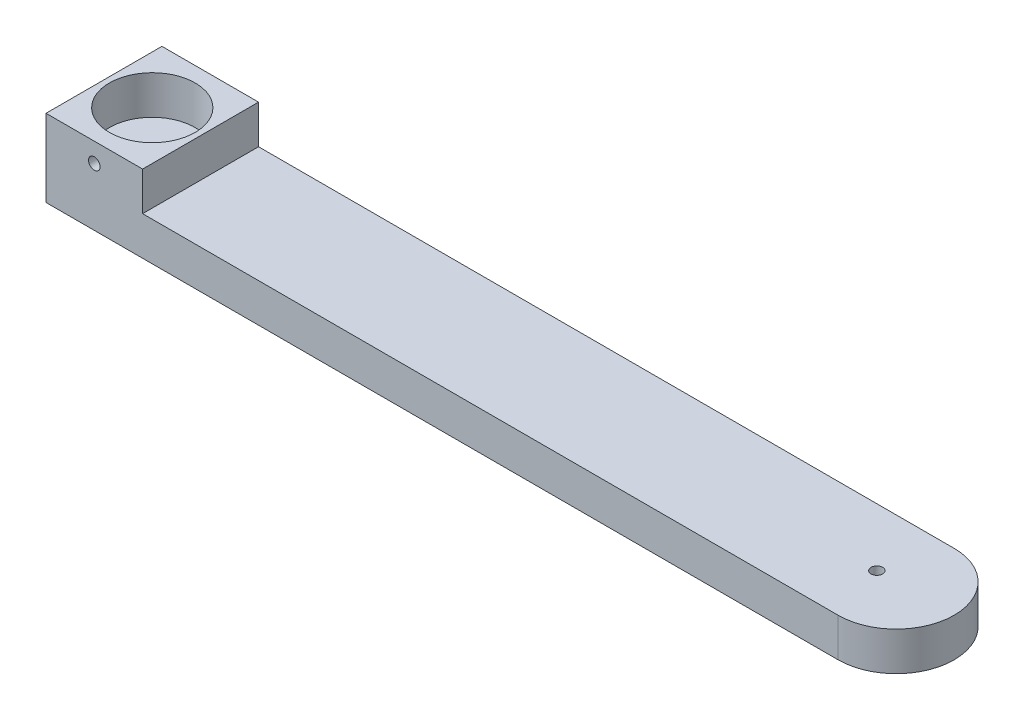
SolidWorks part; units mm, degrees
ref_plane "Front Plane" through (0, 0, 0) normal (0, 0, 1) x (1, 0, 0)
ref_plane "Top Plane" through (0, 0, 0) normal (0, 1, 0) x (1, 0, 0)
ref_plane "Right Plane" through (0, 0, 0) normal (1, 0, 0) x (0, 0, -1)
sketch "Sketch1" plane through (0, 0, 0) normal (0, 1, 0) x (1, 0, 0)
  line L1 (-110, -15) -> (110, -15)
  line L2 (-110, -15) -> (-110, 15)
  line L3 (-110, 15) -> (110, 15)
  line L4 (110, -15) -> (110, 15)
  line L5 (-110, -15) -> (110, 15) construction
  line L6 (-110, 15) -> (110, -15) construction
  circle A0 centre (95, 0) radius 15
  point P0 (0, 0)
  dimension "D3" = 30
  dimension "D1" = 220
  dimension "D2" = 30
extrude "Boss-Extrude1" add sketch "Sketch1" along normal blind 10 contours A0 L3 L2 L1 | A0
sketch "Sketch2" plane through (0, 10, 0) normal (0, 1, 0) x (1, 0, 0)
  line L0 (-5.5, 0) -> (5.5, 0) construction
  line L2 (-85, -15) -> (-110, -15)
  line L3 (-85, -15) -> (-85, 15)
  line L4 (-85, 15) -> (-110, 15)
  line L5 (-110, -15) -> (-110, 15)
  line L6 (-85, -15) -> (-110, 15) construction
  line L7 (-85, 15) -> (-110, -15) construction
  circle A1 centre (-97.5, 0) radius 11.1
  dimension "D1" = 25
  dimension "D2" = 22.2
extrude "Boss-Extrude3" add sketch "Sketch2" along normal blind 10
sketch "Sketch4" plane through (0, 10, 0) normal (0, 1, 0) x (1, 0, 0)
  line L0 (-5.5, 0) -> (5.5, 0) construction
  circle A0 centre (90, 0) radius 4
  arc A1 (95, -15) -> (95, 15) centre (95, 0) ccw construction
  dimension "D1" = 8
  dimension "D2" = 5
sketch "Sketch6" plane through (0, 0, 15) normal (0, 0, 1) x (1, 0, 0)
  line L0 (-85, 10) -> (-110, 10) construction
  line L1 (-110, 20) -> (-110, 0) construction
  line L2 (-97.5, 20) -> (-97.5, 10) construction
  circle A0 centre (-97.5, 15) radius 1.5
  dimension "D1" = 3
extrude "Cut-Extrude2" cut sketch "Sketch6" against normal blind 10
extrude "Cut-Extrude3" cut sketch "Sketch4" along normal blind 6.5 from surface at -10 starting at face at (-3.75, 0, 0)
sketch "Sketch7" plane through (0, 6.5, 0) normal (0, -1, 0) x (-1, 0, 0)
  circle A0 centre (-90, 0) radius 1.5
  dimension "D1" = 3
extrude "Cut-Extrude4" cut sketch "Sketch7" against normal blind 14
sketch "Sketch8" plane through (0, 0, -15) normal (0, 0, -1) x (-1, 0, 0)
  line L0 (-94, 0) -> (-86, 0) construction
  line L1 (-95, 10) -> (-95, 0) construction
  circle A0 centre (-90, 3) radius 1.5
  dimension "D1" = 3
  dimension "D2" = 3
  dimension "D3" = 5
extrude "Cut-Extrude5" cut sketch "Sketch8" against normal up to next
